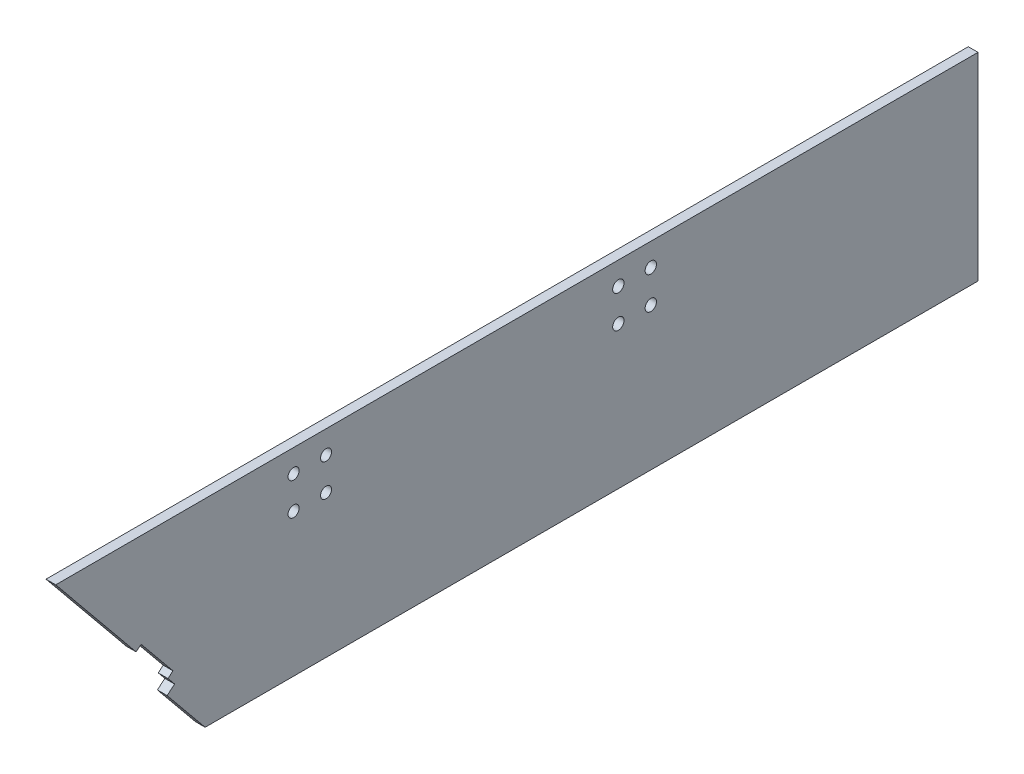
SolidWorks part; units mm, degrees
ref_plane "Front Plane" through (0, 0, 0) normal (0, 0, 1) x (1, 0, 0)
ref_plane "Top Plane" through (0, 0, 0) normal (0, 1, 0) x (1, 0, 0)
ref_plane "Right Plane" through (0, 0, 0) normal (1, 0, 0) x (0, 0, -1)
sketch "Sketch1" plane through (0, 0, 0) normal (0, 0, 1) x (1, 0, 0)
  line L0 (3, 76) -> (3, 0)
  line L2 (0, 0) -> (0, 76)
  line L5 (3, 0) -> (0, 0)
  line L6 (3, 76) -> (0, 76)
  dimension "D1" = 76
  dimension "D2" = 3
extrude "Boss-Extrude1" add sketch "Sketch1" along normal blind 220
hole_wizard "M3 Clearance Hole1" positions "Sketch2" profile "Sketch3" hole size "M3" standard "ANSI Metric" end condition through all
sketch "Sketch2" plane through (0, 0, 0) normal (-1, 0, 0) x (0, 0, 1)
  point P0 (50.7547, 59)
  point P3 (60.7547, 59)
  point P6 (60.7547, 69)
  point P9 (50.7547, 69)
  point P12 (200.7547, 59)
  point P15 (200.7547, 69)
  point P18 (210.7547, 59)
  point P21 (210.7547, 69)
sketch "Sketch3" plane through (0, 59, 50.7547) normal (0, 1, 0) x (0, 0, 1)
  line L0 (0, 0) -> (0, 3)
  line L1 (0, 3) -> (1.7, 3)
  line L2 (1.7, 3) -> (1.7, 0.025)
  line L3 (1.7, 0.025) -> (1.725, 0)
  line L5 (1.725, 0) -> (0, 0)
  line L6 (-1.7, 0.025) -> (-1.725, 0) construction
  line L11 (0, -6.35) -> (0, 107.95) construction
  dimension "Thru Hole Dia." = 3.4
  dimension "Thru Hole Depth" = 3
  dimension "Near C'Sink Dia." = 3.45
  dimension "Near C'Sink Angle" = 90
sketch "Sketch4" plane through (0, 0, 0) normal (-1, 0, 0) x (0, 0, 1)
  line L0 (220, 0) -> (220, 76) construction
  line L1 (0, 0) -> (220, 0)
  line L2 (0, 0) -> (0, 15)
  line L3 (0, 15) -> (220, 15)
  line L4 (220, 0) -> (220, 15)
  dimension "D1" = 15
extrude "Cut-Extrude1" cut sketch "Sketch4" against normal through all
sketch "Sketch5" plane through (0, 0, 0) normal (-1, 0, 0) x (0, 0, 1)
  line L0 (200.7547, 69) -> (110.7547, 69) construction
  line L2 (110.7547, 69) -> (100.7547, 69) construction
  line L3 (110.7547, 69) -> (110.7547, 59) construction
  line L4 (110.7547, 59) -> (100.7547, 59) construction
  line L5 (100.7547, 69) -> (100.7547, 59) construction
  circle A0 centre (200.7547, 69) radius 1.725 construction
  circle A1 centre (200.7547, 69) radius 1.725 construction
  circle A2 centre (110.7547, 69) radius 1.75
  circle A4 centre (100.7547, 69) radius 1.75
  circle A5 centre (100.7547, 59) radius 1.75
  circle A6 centre (110.7547, 59) radius 1.75
  dimension "D2" = 3.5
  dimension "D1" = 90
  dimension "D3" = 10
  dimension "D4" = 10
extrude "Cut-Extrude2" cut sketch "Sketch5" against normal through all
sketch "Sketch6" plane through (0, 0, 0) normal (-1, 0, 0) x (0, 0, 1)
  circle A0 centre (50.7547, 59) radius 1.725 construction
  circle A1 centre (60.7547, 59) radius 1.7 construction
  circle A2 centre (60.7547, 69) radius 1.725 construction
  circle A3 centre (50.7547, 69) radius 1.725 construction
  circle A4 centre (50.7547, 59) radius 1.725
  circle A5 centre (60.7547, 59) radius 1.7
  circle A6 centre (60.7547, 69) radius 1.725
  circle A7 centre (50.7547, 69) radius 1.725
extrude "Boss-Extrude2" add sketch "Sketch6" against normal blind 3
sketch "Sketch7" plane through (0, 0, 0) normal (-1, 0, 0) x (0, 0, 1)
  line L0 (220, 15) -> (0, 15) construction
  line L1 (220, 76) -> (284, 76)
  line L2 (220, 76) -> (220, 15)
  line L3 (220, 15) -> (238, 15)
  line L5 (249.7101, 29.3221) -> (247.3876, 31.2211)
  line L8 (249.7101, 29.3221) -> (238, 15)
  line L9 (247.3876, 31.2211) -> (249.4448, 33.7371)
  line L10 (249.4448, 33.7371) -> (247.8965, 35.0031)
  line L11 (247.8965, 35.0031) -> (257.7076, 47.0027)
  line L12 (257.7076, 47.0027) -> (259.256, 45.7367)
  line L13 (259.256, 45.7367) -> (284, 76)
  dimension "D1" = 64
  dimension "D2" = 18
  dimension "D3" = 3
  dimension "D4" = 18.5
  dimension "D5" = 2
  dimension "D6" = 3.25
  dimension "D7" = 15.5
extrude "Boss-Extrude3" add sketch "Sketch7" against normal blind 3
